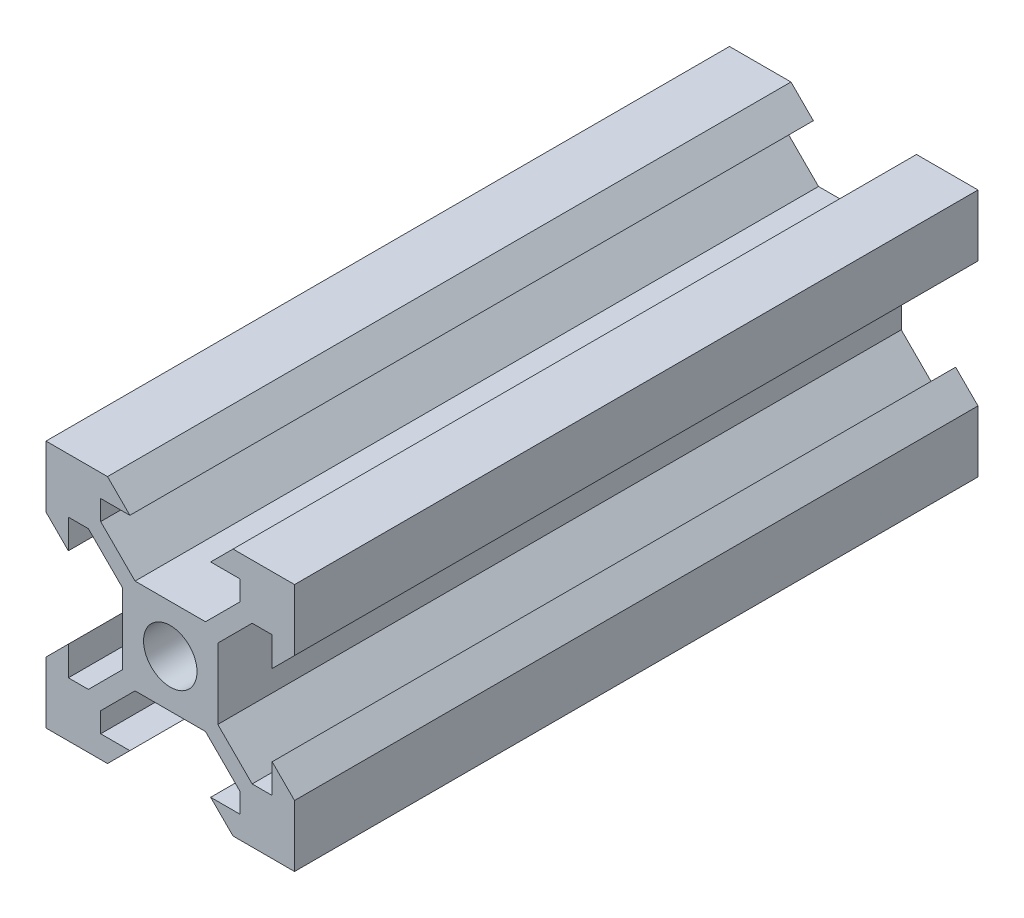
SolidWorks part; units mm, degrees
ref_plane "Alzado" through (0, 0, 0) normal (0, 0, 1) x (1, 0, 0)
ref_plane "Planta" through (0, 0, 0) normal (0, 1, 0) x (1, 0, 0)
ref_plane "Vista lateral" through (0, 0, 0) normal (1, 0, 0) x (0, 0, -1)
sketch "Croquis1" plane through (0, 0, 0) normal (0, 0, 1) x (1, 0, 0)
  line L0 (0, 0) -> (0, -20) construction
  line L2 (0, 0) -> (0, -0.5674)
  line L5 (6.175, -7.1649) -> (6.175, -12.8351)
  line L6 (7.1649, -13.825) -> (12.8351, -13.825)
  line L7 (13.825, -7.1649) -> (13.825, -12.8351)
  line L8 (7.1649, -6.175) -> (12.8351, -6.175)
  line L9 (6.175, -13.825) -> (13.825, -13.825) construction
  line L10 (13.825, -6.175) -> (13.825, -13.825) construction
  line L12 (10, -10) -> (32.1172, -10) construction
  line L13 (13.25, -18.2) -> (15.05, -20)
  line L14 (20, -20) -> (15.6, -20)
  line L15 (20, -20) -> (20, -15.6)
  line L16 (18.2, -15.6) -> (16.5899, -15.6)
  line L32 (15.6, -18.2) -> (15.6, -16.5899)
  line L33 (10, -10) -> (10, -23.2493) construction
  line L34 (4.4, -18.2) -> (4.4, -16.5899)
  line L35 (7.1649, -13.825) -> (4.4, -16.5899)
  line L36 (15.6, -18.2) -> (13.25, -18.2)
  line L38 (15.6, -20) -> (15.05, -20)
  line L40 (15.05, -20) -> (20, -20)
  line L41 (0, -20) -> (20, -20) construction
  line L42 (6.175, -12.8351) -> (3.4101, -15.6)
  line L43 (18.2, -13.25) -> (20, -15.05)
  line L44 (20, -20) -> (18.2, -20)
  line L45 (20, -20) -> (20, -15.05)
  line L48 (20, -15.05) -> (20, -20)
  line L49 (20, 0) -> (20, -20) construction
  line L50 (18.2, -15.6) -> (18.2, -13.25)
  line L51 (12.8351, -13.825) -> (15.6, -16.5899)
  line L52 (13.825, -12.8351) -> (16.5899, -15.6)
  line L53 (1.8, -15.6) -> (3.4101, -15.6)
  line L54 (1.8, -15.6) -> (1.8, -13.25)
  line L55 (1.8, -13.25) -> (0, -15.05)
  line L56 (0, 0) -> (20, 0) construction
  line L57 (0, -20) -> (0, -15.6)
  line L58 (0, -15.6) -> (0, -15.05)
  line L59 (0, -20) -> (4.4, -20)
  line L60 (0, -20) -> (4.95, -20)
  line L61 (6.75, -18.2) -> (4.95, -20)
  line L62 (4.4, -18.2) -> (6.75, -18.2)
  line L63 (1.8, -4.4) -> (3.4101, -4.4)
  line L64 (6.175, -7.1649) -> (3.4101, -4.4)
  line L65 (7.1649, -6.175) -> (4.4, -3.4101)
  line L66 (4.4, -1.8) -> (4.4, -3.4101)
  line L67 (4.4, -1.8) -> (6.75, -1.8)
  line L68 (6.75, -1.8) -> (4.95, 0)
  line L69 (0, 0) -> (4.4, 0)
  line L70 (4.4, 0) -> (4.95, 0)
  line L71 (0, 0) -> (0, -4.4)
  line L72 (0, 0) -> (0, -4.95)
  line L73 (1.8, -6.75) -> (0, -4.95)
  line L74 (1.8, -4.4) -> (1.8, -6.75)
  line L75 (15.6, -1.8) -> (15.6, -3.4101)
  line L76 (12.8351, -6.175) -> (15.6, -3.4101)
  line L77 (13.825, -7.1649) -> (16.5899, -4.4)
  line L78 (18.2, -4.4) -> (16.5899, -4.4)
  line L79 (18.2, -4.4) -> (18.2, -6.75)
  line L80 (18.2, -6.75) -> (20, -4.95)
  line L81 (20, 0) -> (20, -4.4)
  line L82 (20, -4.4) -> (20, -4.95)
  line L83 (20, 0) -> (15.6, 0)
  line L84 (20, 0) -> (15.05, 0)
  line L85 (13.25, -1.8) -> (15.05, 0)
  line L86 (15.6, -1.8) -> (13.25, -1.8)
  line L87 (6.175, -6.175) -> (13.825, -6.175) construction
  line L88 (6.175, -6.175) -> (6.175, -13.825) construction
  circle A0 centre (10, -10) radius 2.15
  point P69 (10, -10)
  dimension "D3" = 4.3
  dimension "D2" = 4
  dimension "D11" = 4.4
  dimension "D15" = 4.4
  dimension "D16" = 6.75
extrude "Saliente-Extruir2" add sketch "Croquis1" along normal blind 55 contours L86 L75 L76 L8 L65 L66 L67 L68 L70 L69 L2 L71 L72 L73 L74 L63 L64 L5 L42 L53 L54 L55 L58 L57 L59 L60 L61 L62 L34 L35 L6 L51 L32 L36 L13 L38 L40 L14 L15 L45 L43 L50 L16 L52 L7 L77 L78 L79 L80 L82 L81
